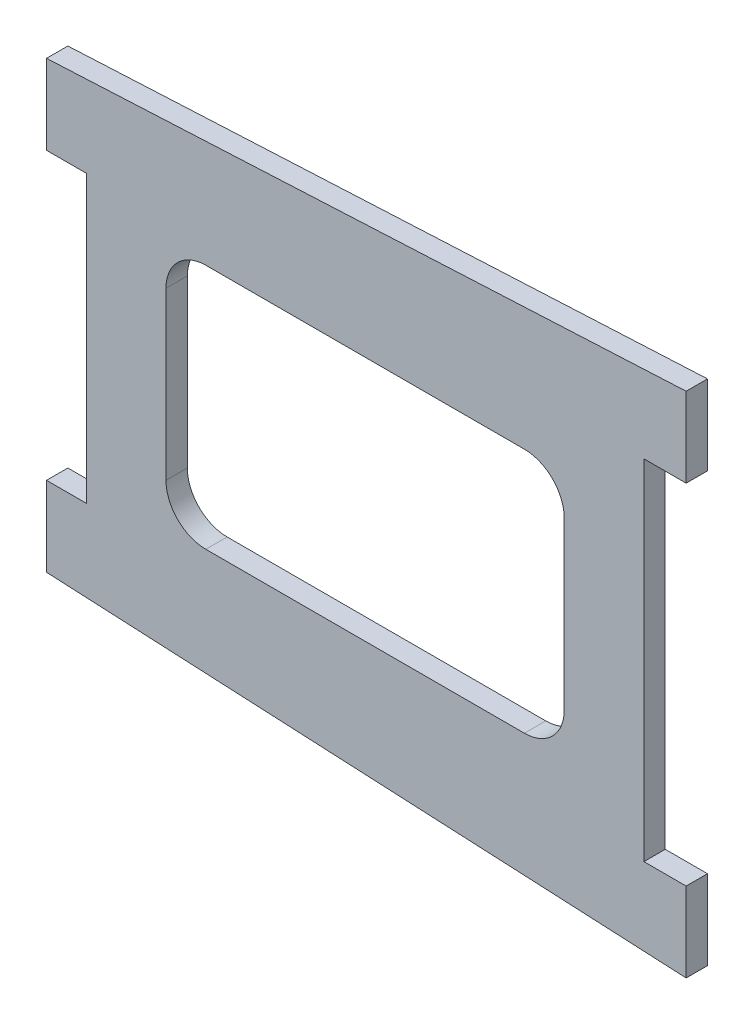
SolidWorks part; units mm, degrees
ref_plane "Front Plane" through (0, 0, 0) normal (0, 0, 1) x (1, 0, 0)
ref_plane "Top Plane" through (0, 0, 0) normal (0, 1, 0) x (1, 0, 0)
ref_plane "Right Plane" through (0, 0, 0) normal (1, 0, 0) x (0, 0, -1)
sketch "Sketch1" plane through (0, 0, 0) normal (0, 0, 1) x (1, 0, 0)
  line L0 (8689.6368, 2979.7501) -> (8587.6482, 2974.7209)
  line L1 (8689.6368, 2898.7241) -> (8587.6482, 2903.7533)
  line L2 (8593.9982, 2962.0209) -> (8593.9982, 2916.4533)
  line L3 (8682.8982, 2967.0501) -> (8682.8982, 2911.4241)
  line L4 (8587.6482, 2916.4533) -> (8593.9982, 2916.4533)
  line L5 (8587.6482, 2916.4533) -> (8587.6482, 2903.7533)
  line L6 (8587.6482, 2962.0209) -> (8593.9982, 2962.0209)
  line L7 (8587.6482, 2962.0209) -> (8587.6482, 2974.7209)
  line L8 (8689.6368, 2911.4241) -> (8682.8982, 2911.4241)
  line L9 (8689.6368, 2911.4241) -> (8689.6368, 2898.7241)
  line L10 (8689.6368, 2967.0501) -> (8682.8982, 2967.0501)
  line L11 (8689.6368, 2967.0501) -> (8689.6368, 2979.7501)
  line L12 (8606.6982, 2952.4959) -> (8606.6982, 2925.9783)
  line L13 (8613.0482, 2958.8459) -> (8663.8482, 2958.8459)
  line L14 (8663.8482, 2919.6283) -> (8613.0482, 2919.6283)
  line L15 (8670.1982, 2952.4959) -> (8670.1982, 2925.9783)
  arc A0 (8613.0482, 2958.8459) -> (8606.6982, 2952.4959) centre (8613.0482, 2952.4959) ccw
  arc A1 (8606.6982, 2925.9783) -> (8613.0482, 2919.6283) centre (8613.0482, 2925.9783) ccw
  arc A2 (8670.1982, 2952.4959) -> (8663.8482, 2958.8459) centre (8663.8482, 2952.4959) ccw
  arc A3 (8663.8482, 2919.6283) -> (8670.1982, 2925.9783) centre (8663.8482, 2925.9783) ccw
extrude "Boss-Extrude1" add sketch "Sketch1" along normal blind 3.4036
